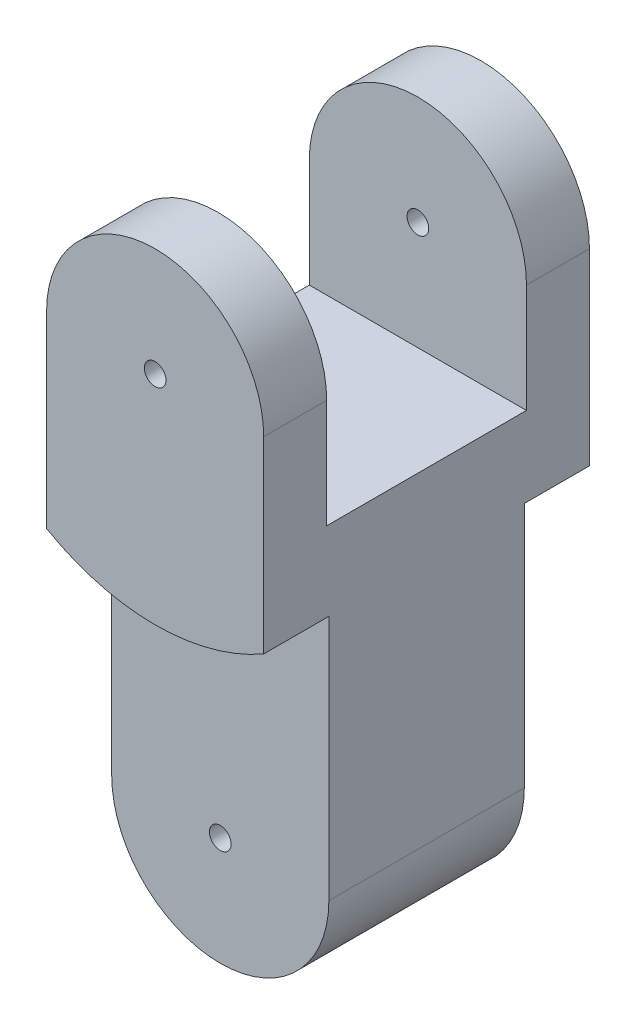
SolidWorks part; units mm, degrees
ref_plane "Ebene vorne" through (0, 0, 0) normal (0, 0, 1) x (1, 0, 0)
ref_plane "Ebene oben" through (0, 0, 0) normal (0, 1, 0) x (1, 0, 0)
ref_plane "Ebene rechts" through (0, 0, 0) normal (1, 0, 0) x (0, 0, -1)
sketch "Skizze1" plane through (0, 0, 0) normal (0, 0, 1) x (1, 0, 0)
  line L0 (-50, 200) -> (-50, 0)
  line L1 (50, 200) -> (50, 0)
  circle A0 centre (0, 0) radius 50
  circle A1 centre (0, 200) radius 50
  circle A2 centre (0, 200) radius 5
  circle A3 centre (0, 0) radius 5
  dimension "D1" = 100
  dimension "D3" = 100
  dimension "D2" = 200
extrude "Aufsatz-Linear austragen1" add sketch "Skizze1" along normal blind 90 contours A1 | A1 L0 A0 L1 | A0
sketch "Skizze2" plane through (0, 0, 90) normal (0, 0, 1) x (1, 0, 0)
  line L0 (-50, 200) -> (-50, 113.3975)
  line L3 (50, 113.3975) -> (50, 200)
  circle A0 centre (0, 200) radius 50
  arc A2 (-50, 113.3975) -> (50, 113.3975) centre (0, 200) ccw
  circle A3 centre (0, 200) radius 5
  arc M4 (50, 200) -> (-50, 200) centre (0, 200) ccw
  line M5 (-50, 200) -> (-50, 0)
  line M7 (50, 0) -> (50, 200)
  circle M8 centre (0, 200) radius 5
extrude "Aufsatz-Linear austragen2" add sketch "Skizze2" along normal blind 30 contours A0 M4 M8 | A2 A0 M5 M7
ref_plane "Ebene1" through (0, 0, 45) normal (0, 0, -1) x (-1, 0, 0)
mirror "Spiegeln1" about plane through (0, 0, 45) normal (0, 0, -1) of "Aufsatz-Linear austragen2"
sketch "Skizze3" plane through (-50, 0, 0) normal (-1, 0, 0) x (0, 0, 1)
  line L0 (-30, 250) -> (-1, 250)
  line L1 (120, 250) -> (-30, 250) construction
  line L2 (120, 250) -> (91, 250)
  line L3 (-1, 250) -> (91, 250)
  line L4 (-1, 250) -> (-1, 150)
  line L5 (-1, 150) -> (91, 150)
  line L6 (91, 250) -> (91, 150)
  line M7 (120, 200) -> (-30, 200)
  line M9 (-30, 113.3975) -> (0, 113.3975)
  line M10 (0, 113.3975) -> (0, 0)
  line M12 (90, 0) -> (90, 113.3975)
  line M13 (90, 113.3975) -> (120, 113.3975)
  dimension "D1" = 29
  dimension "D2" = 29
  dimension "D3" = 100
extrude "Schnitt-Linear austragen1" cut sketch "Skizze3" against normal through all contours L6 L4 L5 M7 M9 M10 M12 M13 | L6 L3 L4 M7
